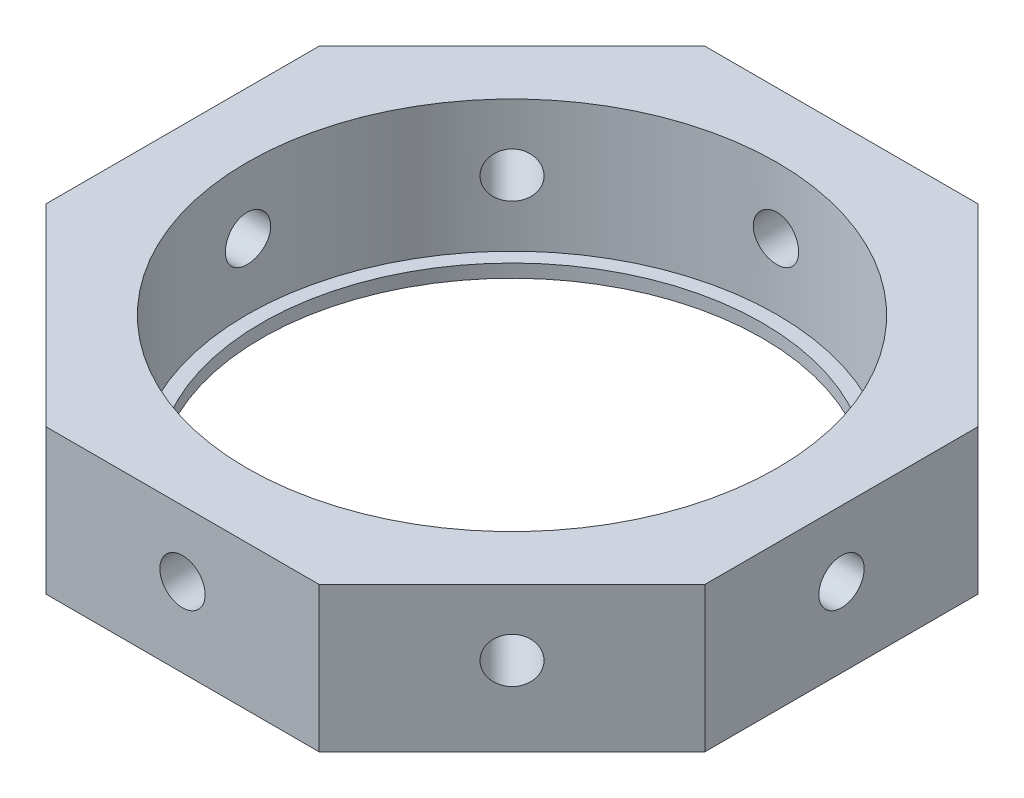
SolidWorks part; units mm, degrees
material "ABS"
ref_plane "Front Plane" through (0, 0, 0) normal (0, 0, 1) x (1, 0, 0)
ref_plane "Top Plane" through (0, 0, 0) normal (0, 1, 0) x (1, 0, 0)
ref_plane "Right Plane" through (0, 0, 0) normal (1, 0, 0) x (0, 0, -1)
sketch "Sketch1" plane through (0, 0, 0) normal (0, 1, 0) x (1, 0, 0)
  line L1 (63.5, 26.3026) -> (26.3026, 63.5)
  line L2 (26.3026, 63.5) -> (-26.3026, 63.5)
  line L3 (-26.3026, 63.5) -> (-63.5, 26.3026)
  line L4 (-63.5, 26.3026) -> (-63.5, -26.3026)
  line L5 (-63.5, -26.3026) -> (-26.3026, -63.5)
  line L6 (-26.3026, -63.5) -> (26.3026, -63.5)
  line L7 (26.3026, -63.5) -> (63.5, -26.3026)
  line L8 (63.5, -26.3026) -> (63.5, 26.3026)
  circle A0 centre (0, 0) radius 51.054
  circle A1 centre (0, 0) radius 63.5 construction
  dimension "D1" = 102.108
  dimension "D2" = 63.5
extrude "Boss-Extrude1" add sketch "Sketch1" along normal blind 25.4
sketch "Sketch2" plane through (63.5, 0, 0) normal (1, 0, 0) x (0, 0, -1)
  circle A0 centre (0, 12.7) radius 4.3656
  dimension "D1" = 8.7312
  dimension "D2" = 12.7
extrude "Cut-Extrude1" cut sketch "Sketch2" against normal blind 31.75
pattern_circular "CirPattern1" count 8 over 360 about axis through (0, 25.4, 0) along (0, -1, 0) of "Cut-Extrude1"
sketch "Sketch3" plane through (0, 0, 0) normal (0, -1, 0) x (1, 0, 0)
  line L1 (26.3026, 63.5) -> (-26.3026, 63.5)
  line L2 (-26.3026, 63.5) -> (-63.5, 26.3026)
  line L3 (-63.5, 26.3026) -> (-63.5, -26.3026)
  line L4 (-63.5, -26.3026) -> (-26.3026, -63.5)
  line L5 (-26.3026, -63.5) -> (26.3026, -63.5)
  line L6 (26.3026, -63.5) -> (63.5, -26.3026)
  line L7 (63.5, -26.3026) -> (63.5, 26.3026)
  line L8 (63.5, 26.3026) -> (26.3026, 63.5)
  circle A0 centre (0, 0) radius 48.26
  circle A1 centre (0, 0) radius 63.5 construction
  dimension "D1" = 96.52
extrude "Boss-Extrude2" add sketch "Sketch3" along normal blind 2.54
